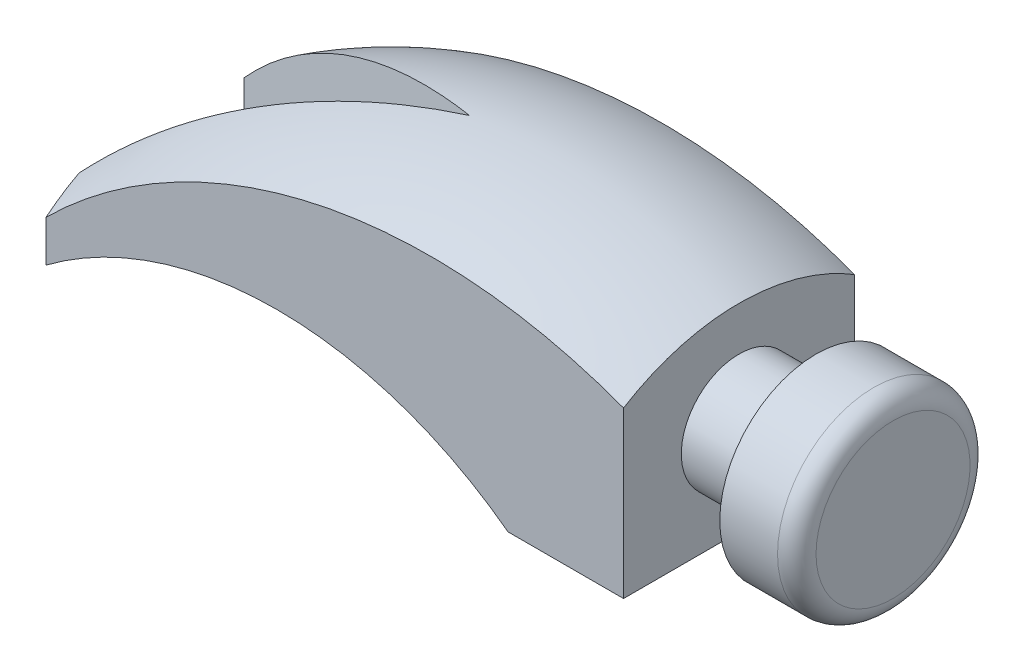
SolidWorks part; units mm, degrees
ref_plane "Front Plane" through (0, 0, 0) normal (0, 0, 1) x (1, 0, 0)
ref_plane "Top Plane" through (0, 0, 0) normal (0, 1, 0) x (1, 0, 0)
ref_plane "Right Plane" through (0, 0, 0) normal (1, 0, 0) x (0, 0, -1)
sketch "Sketch2" plane through (0, 0, 0) normal (0, 0, 1) x (1, 0, 0)
  line L1 (-60, 80) -> (-60, 101.8034)
  line L2 (110, 80) -> (130, 80)
  line L3 (110, 80) -> (110, 90)
  line L4 (110, 130) -> (130, 130)
  line L5 (130, 80) -> (130, 130)
  line L6 (90, 120) -> (90, 131.4214)
  line L7 (110, 120) -> (110, 130)
  line L8 (60, 80) -> (90, 80)
  line L9 (90, 80) -> (90, 90)
  line L10 (120, 105) -> (93.8516, 105) construction
  line L11 (90, 120) -> (110, 120)
  line L12 (90, 90) -> (110, 90)
  arc A0 (60, 80) -> (-60, 80) centre (0, 0) ccw
  arc A1 (90, 131.4214) -> (-60, 101.8034) centre (40, -10) ccw
  point P1 (0, 0)
  point P10 (120, 105)
  point P20 (89.9657, 78.5665)
  dimension "D1" = 200
  dimension "D3" = 300
  dimension "D6" = 200
  dimension "D2" = 120
  dimension "D4" = 90
  dimension "D5" = 20
  dimension "D7" = 50
  dimension "D8" = 90
  dimension "D9" = 190
  dimension "D10" = 25
  dimension "D11" = 20
  dimension "D12" = 15
  dimension "D13" = 20
extrude "Boss-Extrude1" add sketch "Sketch2" along normal mid plane 60
sketch "Sketch3" plane through (130, 0, 0) normal (1, 0, 0) x (0, 0, -1)
  line L2 (30, 80) -> (30, 130) construction
  line L3 (-30, 130) -> (30, 130) construction
  circle A0 centre (0, 105) radius 25
  dimension "D1" = 50
  dimension "D2" = 30
extrude "Cut-Extrude1" cut sketch "Sketch3" against normal up to surface (40 mm away) flip side to cut up to face at (90, 125.7107, 0)
sketch "Sketch4" plane through (130, 0, 0) normal (1, 0, 0) x (0, 0, -1)
  circle A0 centre (0, 105) radius 15
  dimension "D1" = 30
extrude "Cut-Extrude2" cut sketch "Sketch4" against normal blind 20 from surface at -20 flip side to cut starting at face at (110, 125, 0)
fillet "Fillet1" radius 5 1 edges at (130, 105, -25)
sketch "Sketch5" plane through (0, 80, 0) normal (0, -1, 0) x (1, 0, 0)
  line L0 (0, 0) -> (-63.7412, 0) construction
  line L1 (20, 0) -> (-60, 21.4359)
  line L2 (-60, 30) -> (-60, -30) construction
  line L4 (60, 30) -> (-60, 30) construction
  line L5 (20, 0) -> (-60, -21.4359)
  line L6 (-60, -21.4359) -> (-60, 21.4359)
  dimension "D1" = 80
  dimension "D2" = 15
  dimension "D3" = 30
extrude "Cut-Extrude3" cut sketch "Sketch5" against normal up to next
ref_plane "Plane1" through (40, 0, 0) normal (1, 0, 0) x (0, 0, -1)
sketch "Sketch6" plane through (40, 0, 0) normal (1, 0, 0) x (0, 0, -1)
  line L5 (0, 20) -> (0, 80)
  line L6 (0, 80) -> (60, 80)
  arc A0 (60, 80) -> (0, 20) centre (0, 80) ccw
  dimension "D1" = 120
  dimension "D4" = 0
sketch "Sketch7" plane through (0, 0, 0) normal (0, 0, 1) x (1, 0, 0)
  arc A0 (104.3476, 125.4968) -> (-85.5866, 72.0244) centre (40, -10) ccw
  point P1 (104.3476, 125.4968)
  point P4 (0, 0)
  dimension "D1" = 300
surface "Surface-Sweep1"
other "SurfaceCut4"
